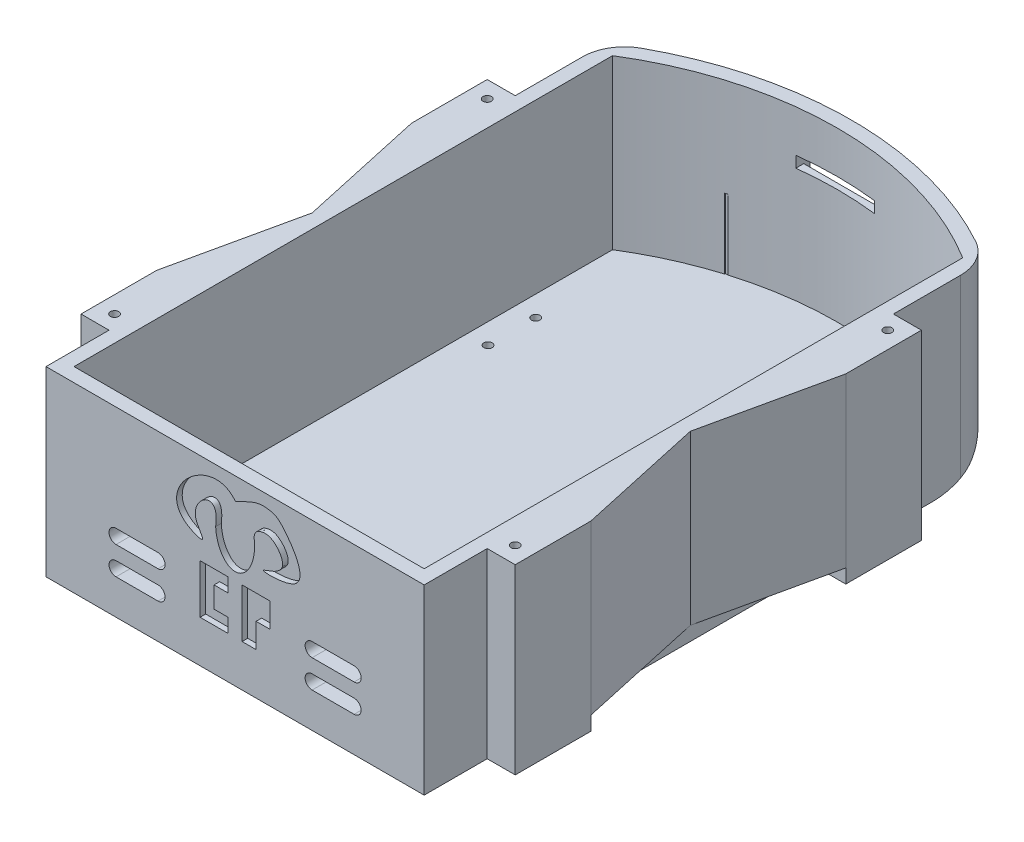
SolidWorks part; units mm, degrees
ref_plane "Alzado" through (0, 0, 0) normal (0, 0, 1) x (1, 0, 0)
ref_plane "Planta" through (0, 0, 0) normal (0, 1, 0) x (1, 0, 0)
ref_plane "Vista lateral" through (0, 0, 0) normal (1, 0, 0) x (0, 0, -1)
sketch "Croquis1" plane through (0, 0, 0) normal (0, 1, 0) x (1, 0, 0)
  line L0 (-67.5, -95) -> (67.5, -95)
  line L2 (67.5, 105) -> (67.5, -95)
  line L4 (-67.5, 105) -> (-67.5, -95)
  line L5 (67.5, 105) -> (-67.5, -105) construction
  line L6 (61.0714, -95) -> (-67.5, 105) construction
  arc A0 (-67.5, 105) -> (67.5, 105) centre (0, 1.0938) cw
  point P0 (0, 0)
  point P3 (0, -95)
  point P7 (0, 125)
  point P8 (-67.5, -100)
  point P9 (0, 0)
  point P11 (-68.9815, -100)
  point P12 (56.7235, -88.2365)
  point P15 (-63.3257, -93.5895)
  point P16 (-68.5788, -98.2971)
  point P17 (-67.6374, -104.4745)
  point P18 (0, 0)
  point P19 (-49.9028, -82.3795)
  point P20 (67.5, -99.022)
  point P21 (64.5498, -100)
  point P22 (-67.5, -105)
  dimension "D1" = 135
  dimension "D2" = 200
  dimension "D3" = 20
  dimension "D4" = 105
extrude "Saliente-Extruir1" add sketch "Croquis1" along normal blind 5
sketch "Croquis2" plane through (0, 5, 0) normal (0, 1, 0) x (1, 0, 0)
  line L0 (-67.5, 105) -> (-67.5, -95) construction
  line L1 (-67.5, 72.5) -> (-77.5, 72.5)
  line L2 (-67.5, 72.5) -> (-67.5, 45.5)
  line L3 (-67.5, 45.5) -> (-77.5, 45.5)
  line L4 (-77.5, 72.5) -> (-77.5, 45.5)
  line L5 (-145.528, 0) -> (168.4635, 0) construction
  line L6 (-67.5, -72.5) -> (-77.5, -72.5)
  line L7 (-67.5, -72.5) -> (-67.5, -45.5)
  line L8 (-67.5, -45.5) -> (-77.5, -45.5)
  line L9 (-77.5, -72.5) -> (-77.5, -45.5)
  line L10 (0, -118.1569) -> (0, 130.279) construction
  line L11 (-77.5, 109) -> (-77.5, 9) construction
  line L12 (-77.5, -8.2769) -> (-77.5, -109.7231) construction
  line L13 (67.5, -45.5) -> (77.5, -45.5)
  line L14 (77.5, -72.5) -> (77.5, -45.5)
  line L15 (67.5, -72.5) -> (77.5, -72.5)
  line L16 (67.5, -72.5) -> (67.5, -45.5)
  line L17 (67.5, 45.5) -> (77.5, 45.5)
  line L18 (77.5, 72.5) -> (77.5, 45.5)
  line L19 (67.5, 72.5) -> (77.5, 72.5)
  line L20 (67.5, 72.5) -> (67.5, 45.5)
  point P17 (-77.5, 59)
  point P18 (-77.5, 59)
  point P21 (-77.5, -59)
  point P23 (-77.5, -59)
  dimension "D1" = 27
  dimension "D2" = 27
  dimension "D3" = 10
  dimension "D4" = 10
  dimension "D5" = 100
  dimension "D7" = 145
extrude "Saliente-Extruir2" add sketch "Croquis2" against normal blind 5 separate body
sketch "Croquis4" plane through (0, 5, 0) normal (0, 1, 0) x (1, 0, 0)
  line L4 (67.5, -45.5) -> (67.5, -72.5)
  line L5 (67.5, -72.5) -> (77.5, -72.5)
  line L6 (77.5, -72.5) -> (77.5, -45.5)
  line L7 (77.5, -45.5) -> (67.5, -45.5)
  line L9 (67.5, -72.5) -> (77.5, -72.5)
  line L10 (77.5, -72.5) -> (77.5, -45.5)
  line L11 (77.5, -45.5) -> (67.5, -45.5)
  line L12 (-67.5, 45.5) -> (-67.5, 72.5)
  line L13 (-67.5, 72.5) -> (-77.5, 72.5)
  line L14 (-77.5, 72.5) -> (-77.5, 45.5)
  line L15 (-77.5, 45.5) -> (-67.5, 45.5)
  line L17 (-67.5, 72.5) -> (-77.5, 72.5)
  line L18 (-77.5, 72.5) -> (-77.5, 45.5)
  line L19 (-77.5, 45.5) -> (-67.5, 45.5)
  line L32 (-90.4519, 0) -> (97.068, 0) construction
  line L33 (67.5, 45.5) -> (67.5, 72.5)
  line L34 (77.5, 45.5) -> (67.5, 45.5)
  line L35 (77.5, 72.5) -> (77.5, 45.5)
  line L40 (67.5, -45.5) -> (67.5, -72.5)
  line L41 (-67.5, 45.5) -> (-67.5, 72.5)
  line L42 (67.5, 72.5) -> (77.5, 72.5)
  line L43 (-67.5, -45.5) -> (-67.5, -72.5)
  line L44 (-77.5, -45.5) -> (-67.5, -45.5)
  line L45 (-77.5, -72.5) -> (-77.5, -45.5)
  line L46 (-67.5, -72.5) -> (-77.5, -72.5)
  dimension "D1" = 0
  dimension "D2" = 0
extrude "Saliente-Extruir5" add sketch "Croquis4" along normal blind 80
sketch "Croquis12" plane through (0, 5, 0) normal (0, 1, 0) x (1, 0, 0)
  line L11 (-67.5, -45.5) -> (-67.5, -72.5)
  line L12 (-67.5, -45.5) -> (-67.5, -72.5)
  line L13 (67.5, -72.5) -> (67.5, -45.5)
  line L14 (67.5, -72.5) -> (67.5, -45.5)
  line L15 (67.5, -45.5) -> (67.5, 45.5)
  line L16 (-67.5, -72.5) -> (-67.5, -95)
  line L17 (67.5, -45.5) -> (67.5, 45.5)
  line L18 (67.5, 45.5) -> (67.5, 72.5)
  line L19 (-67.5, -95) -> (67.5, -95)
  line L20 (67.5, 45.5) -> (67.5, 72.5)
  line L21 (67.5, 72.5) -> (67.5, 105)
  line L22 (67.5, -95) -> (67.5, -72.5)
  line L23 (67.5, 72.5) -> (67.5, 105)
  line L24 (-67.5, 105) -> (-67.5, 72.5)
  line L25 (-67.5, 105) -> (-67.5, 72.5)
  line L26 (-67.5, 72.5) -> (-67.5, 45.5)
  line L27 (-67.5, 72.5) -> (-67.5, 45.5)
  line L28 (-67.5, 45.5) -> (-67.5, -45.5)
  line L29 (-67.5, 45.5) -> (-67.5, -45.5)
  line L31 (-67.5, -72.5) -> (-67.5, -95)
  line L34 (-67.5, -95) -> (67.5, -95)
  line L37 (67.5, -95) -> (67.5, -72.5)
  arc A5 (67.5, 105) -> (-67.5, 105) centre (0, 1.0938) ccw
  arc A8 (67.5, 105) -> (-67.5, 105) centre (0, 1.0938) ccw
  dimension "D1" = 0
extrude "Extruir-Lámina4" add sketch "Croquis12" along normal blind 80 thin thin type one direction reverse wall 5
sketch "Croquis14" plane through (0, 85, 0) normal (0, 1, 0) x (1, 0, 0)
  line L1 (-77.5, 45.5) -> (-67.5, 0)
  line L3 (74.2489, 0) -> (-102.1603, 0) construction
  line L4 (-67.5, 45.5) -> (-67.5, -45.5) construction
  line L5 (0, -56.0609) -> (0, 58.5982) construction
  line L6 (-67.5, -45.5) -> (-77.5, -45.5) construction
  line L7 (-77.5, 45.5) -> (-67.5, 45.5) construction
  line L8 (-67.5, -45.5) -> (-77.5, -45.5)
  line L10 (-77.5, 45.5) -> (-67.5, 45.5)
  line L11 (-77.5, -45.5) -> (-67.5, 0)
  line L12 (-67.5, -45.5) -> (-67.5, 0)
  line L13 (-67.5, 0) -> (-67.5, 45.5)
  line L14 (67.5, -45.5) -> (67.5, 0)
  line L15 (67.5, -45.5) -> (77.5, -45.5)
  line L16 (77.5, -45.5) -> (67.5, 0)
  line L17 (77.5, 45.5) -> (67.5, 0)
  line L18 (77.5, 45.5) -> (67.5, 45.5)
  line L19 (67.5, 0) -> (67.5, 45.5)
  line M9 (77.5, -45.5) -> (67.5, -45.5)
  line M10 (67.5, -45.5) -> (67.5, 45.5)
  line M11 (67.5, 45.5) -> (77.5, 45.5)
  line M20 (-67.5, 45.5) -> (-67.5, -45.5)
  line M21 (-67.5, -45.5) -> (-77.5, -45.5)
extrude "Saliente-Extruir6" add sketch "Croquis14" against normal blind 80 contours L17 M11 M10 | L16 M9 M10 | L11 M21 M20 | L13 L10 L1
fillet "Redondeo3" radius 15 3 edges at (-67.5, 42.5, -105) (0, 0, -125) (67.5, 42.5, -105)
sketch "Croquis15" plane through (0, 0, 0) normal (1, 0, 0) x (0, 0, -1)
  line L0 (125, 15) -> (125, 85) construction
  line L1 (-95, 85) -> (125, 85)
  line L2 (-95, 85) -> (-95, 65)
  line L3 (-95, 65) -> (125, 65)
  line L4 (125, 85) -> (125, 65)
  line L5 (-95, 85) -> (-72.5, 85) construction
  line L6 (-95, 85) -> (-95, 0) construction
  point P7 (-100, 85)
  dimension "D1" = 20
extrude "Cortar-Extruir2" cut sketch "Croquis15" against normal mid plane 200
sketch "Croquis16" plane through (0, 65, 0) normal (0, 1, 0) x (1, 0, 0)
  line L43 (67.5, -72.5) -> (77.5, -72.5) construction
  line L44 (77.5, -72.5) -> (77.5, -45.5) construction
  line L45 (0, -90) -> (0, 13.2247) construction
  line L46 (62.5, -90) -> (-62.5, -90) construction
  line L47 (0, 52.9303) -> (0, 51.9276) construction
  line L48 (-51.1719, 0) -> (87.1961, 0) construction
  circle A10 centre (71.5, -66.5) radius 1.5
  circle A11 centre (71.5, 66.5) radius 1.5
  circle A12 centre (-71.5, -66.5) radius 1.5
  circle A13 centre (-71.5, 66.5) radius 1.5
  dimension "D1" = 3
  dimension "D2" = 6
  dimension "D3" = 6
extrude "Cortar-Extruir3" cut sketch "Croquis16" against normal mid plane 20
sketch "Croquis17" plane through (0, 0, 0) normal (0, -1, 0) x (1, 0, 0)
  line L0 (67.5, 45.5) -> (67.5, -45.5) construction
  line L1 (-67.5, -45.5) -> (-67.5, 45.5) construction
  line L2 (67.5, 45.5) -> (67.5, -45.5)
  line L3 (-67.5, -45.5) -> (-67.5, 45.5)
extrude "Extruir-Lámina5" add sketch "Croquis17" along normal blind 20 thin
sketch "Croquis18" plane through (0, 0, 0) normal (0, -1, 0) x (1, 0, 0)
  line L0 (62.5, 45.5) -> (-62.5, 45.5)
  line L1 (-62.5, -45.5) -> (-62.5, 45.5) construction
  line L2 (-62.5, 0) -> (62.5, 0) construction
  line L3 (62.5, 45.5) -> (62.5, -45.5) construction
  line L4 (-62.5, -45.5) -> (62.5, -45.5)
extrude "Extruir-Lámina6" add sketch "Croquis18" along normal blind 20 thin thin type one direction reverse wall 5
sketch "Croquis19" plane through (0, 0, -45.5) normal (0, 0, -1) x (-1, 0, 0)
  line L0 (0, 0) -> (0, -20) construction
  line L1 (-67.5, -20) -> (67.5, -20) construction
  line L2 (-45, -10) -> (45, -10) construction
  line L3 (-45, -5) -> (45, -5)
  line L4 (-45, -15) -> (45, -15)
  arc A0 (-45, -5) -> (-45, -15) centre (-45, -10) ccw
  arc A1 (45, -15) -> (45, -5) centre (45, -10) ccw
  point P7 (0, -10)
  dimension "D1" = 5
  dimension "D2" = 90
extrude "Cortar-Extruir4" cut sketch "Croquis19" against normal through all
sketch "Croquis20" plane through (0, 5, 0) normal (0, 1, 0) x (1, 0, 0)
  line L0 (0, -72.8589) -> (0, 120) construction
  line L2 (30, 110) -> (-30, 110)
  line L3 (30, 110) -> (30, 20)
  line L4 (30, 20) -> (-30, 20)
  line L5 (-30, 110) -> (-30, 20)
  line L6 (30, 110) -> (-30, 20) construction
  line L7 (30, 20) -> (-30, 110) construction
  arc A0 (62.5, 102.2493) -> (-62.5, 102.2493) centre (0, 1.0938) ccw construction
  point P5 (0, 65)
  dimension "D1" = 90
  dimension "D2" = 60
  dimension "D3" = 65
extrude "Extruir-Lámina7" add sketch "Croquis20" along normal blind 25 thin
sketch "Croquis21" plane through (0, 30, 0) normal (0, 1, 0) x (1, 0, 0)
  line L0 (49.1479, -8.9914) -> (49.1479, 109.3674) construction
  line L1 (-30, 65) -> (30, 65) construction
  line L2 (-30, 110) -> (-30, 20) construction
  line L3 (30, 20) -> (30, 110) construction
  line L5 (-30, 65) -> (-30, 20) construction
  line L6 (0, 0) -> (0, 120) construction
  line L7 (-35, 15) -> (35, 15) construction
  line L8 (-35, 114.7322) -> (-35, 15) construction
  arc A0 (62.5, 102.2493) -> (35, 114.7322) centre (0, 1.0938) ccw construction
  arc A1 (62.5, 102.2493) -> (-62.5, 102.2493) centre (0, 1.0938) ccw construction
  circle A2 centre (-32.5, 21) radius 1.5
  circle A3 centre (32.5, 21) radius 1.5
  circle A4 centre (32.5, 109) radius 1.5
  circle A5 centre (-32.5, 109) radius 1.5
  dimension "D1" = 3
  dimension "D2" = 2.5
  dimension "D3" = 6
extrude "Cortar-Extruir5" cut sketch "Croquis21" against normal blind 15
sketch "Croquis23" plane through (0, 0, 95) normal (0, 0, 1) x (1, 0, 0)
  line L0 (0, 0) -> (0, 65) construction
  line L1 (-67.5, 65) -> (67.5, 65) construction
  line L2 (42.5, 65) -> (42.5, 0) construction
  line L3 (67.5, 65) -> (67.5, 0) construction
  ellipse E1 centre (0, 46.736) end of major axis (0, 35.3725) minor radius 6.9654 (-6.9413, 45.7927) -> (6.9478, 47.5417) ccw
  spline S0 degree 3 poles (-6.9413, 45.7927) (-5.1907, 57.9564) (-19.405, 48.9758) (-8.6654, 37.4465) (-32.7837, 46.6854) (-7.8236, 67.7673) (0.1589, 57.0756) knots 0 0 0 0 0.267888 0.369213 0.489808 1 1 1 1
  spline S2 degree 3 poles (6.9478, 47.5417) (6.7105, 49.5523) (6.3679, 52.0909) (13.4143, 52.9118) (21.2588, 43.0732) (2.5629, 40.2649) (27.32, 39.8695) (21.4611, 52.6849) (15.2814, 59.7635) (8.9422, 61.4386) (6.511, 60.3267) (0.1589, 57.0756) knots 0.012478 0.012478 0.012478 0.012478 0.104727 0.122183 0.187037 0.309754 0.453793 0.616774 0.68652 0.724843 1 1 1 1
  point P3 (0, 0)
  point P8 (14.4206, 59.8521)
  point P22 (10.9255, 52.5442)
  point P24 (10.1938, 52.5442)
  point P30 (10.6353, 52.5442)
  point P31 (17.169, 46.736)
  point P34 (16.9227, 46.736)
  dimension "D2" = 23.3161
  dimension "D4" = 53.0794
  dimension "D5" = 50.5773
  dimension "D6" = 32.2999
  dimension "D7" = 21.2152
  dimension "D8" = 35.5522
  dimension "D9" = 42.3411
  dimension "D10" = 49.4413
  dimension "D11" = 35.5346
  dimension "D12" = 52.4052
  dimension "D13" = 54.1264
  dimension "D14" = 56.5727
  dimension "D15" = 60.7772
  dimension "D16" = 62.3592
  dimension "D17" = 5.1479
  dimension "D18" = 6.9005
  dimension "D19" = 7.9244
  dimension "D20" = 10.0453
  dimension "D21" = 12.4558
  dimension "D22" = 13.2748
  dimension "D23" = 17.4583
  dimension "D24" = 22.7523
  dimension "D25" = 56.8647
  dimension "D26" = 19.923
  dimension "D27" = 22.7515
  dimension "D29" = 24.1284
  dimension "D30" = 25.4271
sketch "Croquis25" plane through (0, 0, 95) normal (0, 0, 1) x (1, 0, 0)
  line L0 (-2.5, 15) -> (-12.5, 15)
  line L1 (-12.5, 15) -> (-12.5, 32.5)
  line L2 (-12.5, 32.5) -> (-2.5, 32.5)
  line L3 (-2.5, 32.5) -> (-2.5, 27.5)
  line L4 (-2.5, 27.5) -> (-7.5, 27.5)
  line L5 (-7.5, 27.5) -> (-7.5, 20)
  line L6 (-7.5, 20) -> (-2.5, 20)
  line L7 (-2.5, 20) -> (-2.5, 15)
  line L8 (2.5, 15) -> (2.5, 32.5)
  line L9 (2.5, 32.5) -> (12.5, 32.5)
  line L10 (12.5, 32.5) -> (12.5, 23.75)
  line L11 (12.5, 23.75) -> (7.5, 23.75)
  line L12 (7.5, 23.75) -> (7.5, 15)
  line L13 (7.5, 15) -> (2.5, 15)
  line L14 (0, 0) -> (0, 65) construction
  line L15 (-67.5, 0) -> (67.5, 0) construction
  line L16 (-67.5, 65) -> (67.5, 65) construction
  line L17 (-16.6241, 15) -> (16.6241, 15) construction
  line L18 (-67.5, 0) -> (67.5, 0) construction
  circle A1 centre (7.5, 28.125) radius 5.0138 construction
  point P22 (0, 15)
  point P27 (12.5, 28.125)
  dimension "D7" = 10.0277
  dimension "D1" = 15
  dimension "D2" = 10
  dimension "D3" = 5
  dimension "D4" = 5
  dimension "D5" = 7.5
  dimension "D6" = 2.5
sketch "Croquis26" plane through (-35, 0, 0) normal (-1, 0, 0) x (0, 0, 1)
  line L0 (-114.7322, 5) -> (-15, 5) construction
  line L1 (-20, 5) -> (-105, 5)
  line L2 (-20, 5) -> (-20, 25)
  line L3 (-20, 25) -> (-105, 25)
  line L4 (-105, 5) -> (-105, 25)
  line L5 (-15, 30) -> (-15, 5) construction
  dimension "D1" = 5
  dimension "D2" = 85
  dimension "D3" = 20
extrude "Cortar-Extruir7" cut sketch "Croquis26" against normal up to next
sketch "Croquis27" plane through (0, 0, -15) normal (0, 0, 1) x (1, 0, 0)
  line L0 (-35, 5) -> (35, 5) construction
  line L1 (-30, 5) -> (30, 5)
  line L2 (-30, 5) -> (-30, 25)
  line L3 (-30, 25) -> (30, 25)
  line L4 (30, 5) -> (30, 25)
  point P6 (0, 25)
  dimension "D1" = 60
  dimension "D2" = 20
extrude "Cortar-Extruir8" cut sketch "Croquis27" against normal up to next
sketch "Croquis28" plane through (0, 0, 0) normal (0, -1, 0) x (1, 0, 0)
  line L0 (-77.5, 59) -> (77.5, 59) construction
  line L1 (-77.5, 45.5) -> (-77.5, 72.5) construction
  line L2 (77.5, 72.5) -> (77.5, 45.5) construction
  line L3 (77.5, 72) -> (77.5, 46) construction
  line L5 (62.5, 59) -> (62.5, 40.6567) construction
  line L6 (0, 0) -> (0, 59) construction
  line L7 (-67.5, 0) -> (67.5, 0) construction
  line L8 (-67.5, -45.5) -> (-67.5, 45.5) construction
  line L9 (67.5, 45.5) -> (67.5, -45.5) construction
  circle A0 centre (69.8, 50.5) radius 1.5
  circle A1 centre (62.5, 59) radius 4.8 construction
  circle A2 centre (69.8, 67.5) radius 1.5
  circle A3 centre (55.2, 50.5) radius 1.5
  circle A4 centre (55.2, 67.5) radius 1.5
  circle A5 centre (-55.2, 67.5) radius 1.5
  circle A6 centre (-69.8, 67.5) radius 1.5
  circle A7 centre (-69.8, 50.5) radius 1.5
  circle A8 centre (-55.2, 50.5) radius 1.5
  circle A9 centre (55.2, -67.5) radius 1.5
  circle A10 centre (69.8, -67.5) radius 1.5
  circle A11 centre (69.8, -50.5) radius 1.5
  circle A12 centre (55.2, -50.5) radius 1.5
  circle A13 centre (-55.2, -67.5) radius 1.5
  circle A14 centre (-69.8, -67.5) radius 1.5
  circle A15 centre (-69.8, -50.5) radius 1.5
  circle A16 centre (-55.2, -50.5) radius 1.5
  point P8 (77.5, 59)
  dimension "D2" = 7.7
  dimension "D4" = 3
  dimension "D5" = 15
  dimension "D6" = 9.6
  dimension "D1" = 26
  dimension "D3" = 4.5
extrude "Cortar-Extruir9" cut sketch "Croquis28" against normal blind 5
sketch "Croquis29" plane through (0, 0, 0) normal (0, 0, 1) x (1, 0, 0)
  line L0 (0, 0) -> (0, 65) construction
  line L1 (59.731, 65) -> (-59.731, 65) construction
  line L2 (59.731, 40) -> (-59.731, 40) construction
  line L3 (14, 50) -> (-14, 50)
  line L4 (14, 50) -> (14, 22)
  line L5 (14, 22) -> (-14, 22)
  line L6 (-14, 50) -> (-14, 22)
  line L7 (14, 50) -> (-14, 22) construction
  line L8 (14, 22) -> (-14, 50) construction
  line L9 (59.731, 65) -> (59.731, 15) construction
  line L10 (-59.731, 15) -> (-59.731, 65) construction
  point P5 (0, 40)
  point P16 (0, 36)
  dimension "D1" = 28
  dimension "D2" = 28
  dimension "D3" = 10
extrude "Cortar-Extruir10" cut sketch "Croquis29" against normal blind 3 from offset 122 offset against normal yes
sketch "Croquis33" plane through (0, 0, -122) normal (0, 0, -1) x (-1, 0, 0)
  line L0 (14, 50) -> (14, 22) construction
  line L1 (-14, 46) -> (14, 46)
  line L2 (-14, 46) -> (-14, 50)
  line L3 (-14, 50) -> (14, 50)
  line L4 (14, 46) -> (14, 50)
  dimension "D1" = 4
extrude "Cortar-Extruir11" cut sketch "Croquis33" against normal blind 50
sketch "Croquis34" plane through (62.5, 0, 0) normal (-1, 0, 0) x (0, 0, 1)
  line L1 (-45.5, 0) -> (45.5, 0)
  line L2 (-45.5, 0) -> (-45.5, -20)
  line L3 (-45.5, -20) -> (45.5, -20)
  line L4 (45.5, 0) -> (45.5, -20)
extrude "Cortar-Extruir12" cut sketch "Croquis34" against normal through all both and the other way through all
sketch "Croquis35" plane through (0, 0, -15) normal (0, 0, 1) x (1, 0, 0)
  line L0 (-35, 30) -> (35, 30) construction
  line L1 (-30, 25) -> (30, 25)
  line L2 (-30, 25) -> (-30, 30)
  line L3 (-30, 30) -> (30, 30)
  line L4 (30, 25) -> (30, 30)
extrude "Cortar-Extruir13" cut sketch "Croquis35" against normal up to next
sketch "Croquis36" plane through (0, 0, -15) normal (0, 0, 1) x (1, 0, 0)
  line L0 (30, 30) -> (35, 30) construction
  line L1 (-35, 5) -> (35, 5)
  line L2 (-35, 5) -> (-35, 30)
  line L3 (-35, 30) -> (35, 30)
  line L4 (35, 5) -> (35, 30)
  line L5 (35, 30) -> (35, 5) construction
extrude "Cortar-Extruir14" cut sketch "Croquis36" against normal blind 100
sketch "Croquis37" plane through (0, 0, 95) normal (0, 0, 1) x (1, 0, 0)
  line L0 (0, 0) -> (0, 65) construction
  line L1 (-67.5, 0) -> (67.5, 0) construction
  line L2 (-67.5, 65) -> (67.5, 65) construction
  line L3 (-45, 15) -> (43.9353, 15) construction
  line L6 (-45, 20) -> (40, 20) construction
  line L8 (-42.5, 15) -> (-27.5, 15) construction
  line L9 (-42.5, 17.5) -> (-27.5, 17.5)
  line L10 (-42.5, 12.5) -> (-27.5, 12.5)
  line L11 (-42.5, 25) -> (-27.5, 25) construction
  line L12 (-42.5, 22.5) -> (-27.5, 22.5)
  line L13 (-42.5, 27.5) -> (-27.5, 27.5)
  line L14 (42.5, 15) -> (27.5, 15) construction
  line L15 (42.5, 17.5) -> (27.5, 17.5)
  line L16 (42.5, 12.5) -> (27.5, 12.5)
  line L17 (42.5, 25) -> (27.5, 25) construction
  line L18 (42.5, 22.5) -> (27.5, 22.5)
  line L19 (42.5, 27.5) -> (27.5, 27.5)
  arc A0 (-42.5, 17.5) -> (-42.5, 12.5) centre (-42.5, 15) ccw
  arc A1 (-27.5, 12.5) -> (-27.5, 17.5) centre (-27.5, 15) ccw
  arc A2 (-42.5, 22.5) -> (-42.5, 27.5) centre (-42.5, 25) cw
  arc A3 (-27.5, 27.5) -> (-27.5, 22.5) centre (-27.5, 25) cw
  arc A4 (42.5, 17.5) -> (42.5, 12.5) centre (42.5, 15) cw
  arc A5 (27.5, 12.5) -> (27.5, 17.5) centre (27.5, 15) cw
  arc A6 (42.5, 22.5) -> (42.5, 27.5) centre (42.5, 25) ccw
  arc A7 (27.5, 27.5) -> (27.5, 22.5) centre (27.5, 25) ccw
  point P8 (46.4353, 15)
  point P18 (-35, 15)
  point P25 (-35, 25)
  point P32 (35, 15)
  point P39 (35, 25)
  dimension "D3" = 2.5
  dimension "D1" = 15
  dimension "D2" = 5
  dimension "D4" = 15
  dimension "D5" = 35
extrude "Cortar-Extruir15" cut sketch "Croquis37" against normal up to next
sketch "Croquis38" plane through (0, 0, 0) normal (0, 1, 0) x (1, 0, 0)
  line L0 (0, -90) -> (0, 120) construction
  line L1 (62.5, -90) -> (-62.5, -90) construction
  line L2 (-62.5, 0) -> (62.5, 0) construction
  line L5 (-62.5, 102.2493) -> (-62.5, -90) construction
  line L6 (62.5, 102.2493) -> (62.5, -90) construction
  arc A0 (62.5, 102.2493) -> (-62.5, 102.2493) centre (0, 1.0938) ccw construction
  dimension "D1" = 125
  dimension "D2" = 210
extrude "Cortar-Extruir16" cut sketch "Croquis23" against normal blind 2
extrude "Cortar-Extruir17" cut sketch "Croquis25" against normal blind 2
